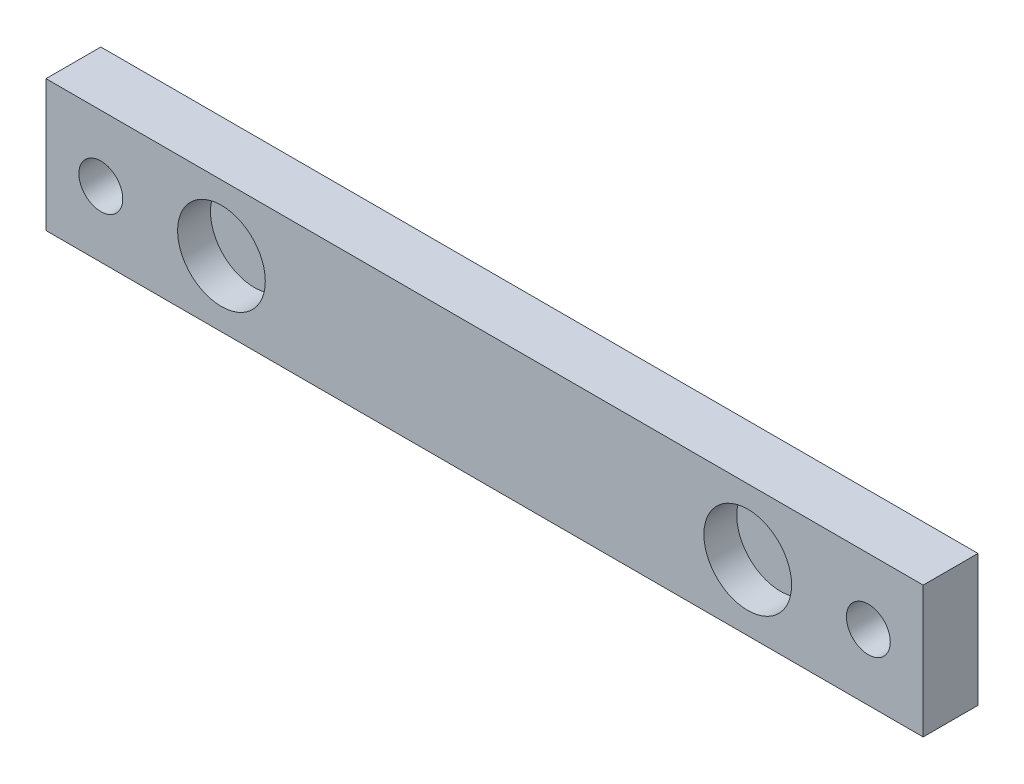
SolidWorks part; units mm, degrees
ref_plane "Front Plane" through (0, 0, 0) normal (0, 0, 1) x (1, 0, 0)
ref_plane "Top Plane" through (0, 0, 0) normal (0, 1, 0) x (1, 0, 0)
ref_plane "Right Plane" through (0, 0, 0) normal (1, 0, 0) x (0, 0, -1)
sketch "Sketch1" plane through (0, 0, 0) normal (0, 0, 1) x (1, 0, 0)
  line L0 (-50, 6) -> (-50, -6)
  line L5 (30, -6) -> (30, 6)
  line L6 (30, 6) -> (-50, 6)
  line L9 (-50, -6) -> (30, -6)
  circle A0 centre (-34, 0) radius 4
  circle A2 centre (14, 0) radius 4
  circle A3 centre (-45, 0) radius 2
  circle A4 centre (25, 0) radius 2
  point P12 (0, 0)
  dimension "D10" = 8
  dimension "D9" = 8
  dimension "D8" = 4
  dimension "D13" = 4
  dimension "D2" = 12
  dimension "D3" = 6
  dimension "D4" = 80
  dimension "D5" = 30
  dimension "D6" = 6
  dimension "D7" = 16
  dimension "D11" = 48
  dimension "D12" = 5
  dimension "D14" = 70
  dimension "D15" = 6
extrude "Boss-Extrude1" add sketch "Sketch1" along normal blind 5
sketch "Sketch2" plane through (0, 0, 0) normal (0, 0, -1) x (-1, 0, 0)
  circle A0 centre (34, 0) radius 4 construction
  circle A1 centre (34, 0) radius 4
  circle A2 centre (-14, 0) radius 4 construction
  circle A3 centre (-14, 0) radius 4
extrude "Boss-Extrude2" add sketch "Sketch2" against normal blind 2
